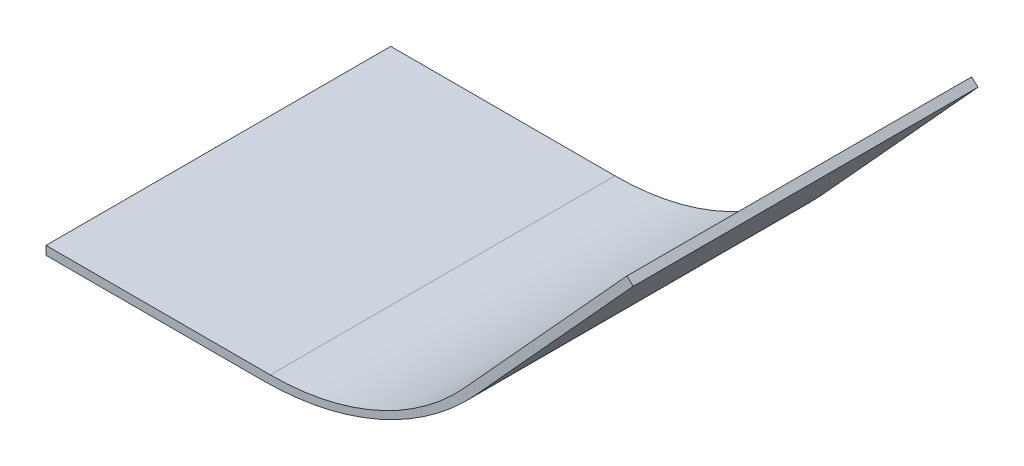
SolidWorks part; units mm, degrees
ref_plane "Front Plane" through (0, 0, 0) normal (0, 0, 1) x (1, 0, 0)
ref_plane "Top Plane" through (0, 0, 0) normal (0, 1, 0) x (1, 0, 0)
ref_plane "Right Plane" through (0, 0, 0) normal (1, 0, 0) x (0, 0, -1)
sketch "Sketch2" plane through (0, 0, 0) normal (0, 0, 1) x (1, 0, 0)
  line L0 (-10, 0.25) -> (-10, -0.25)
  line L1 (-10, 0.25) -> (3.0144, 0.25)
  line L2 (-10, -0.25) -> (2.5586, -0.25)
  line L4 (23.7043, 15.5673) -> (24.0738, 15.2305)
  line L5 (23.7043, 15.5673) -> (14.2726, 5.2211)
  line L6 (24.0738, 15.2305) -> (14.9492, 5.2211)
  arc A0 (2.5586, -0.25) -> (14.9492, 5.2211) centre (2.5586, 16.5164) ccw
  arc A1 (3.0144, 0.25) -> (14.2726, 5.2211) centre (3.0144, 15.4841) ccw
  point P14 (12.6919, 2.7449)
  point P15 (12.2182, 2.9674)
  point P16 (0, 0)
  point P17 (0, 0)
  point P18 (2.5586, 16.5164)
  point P19 (2.5586, -0.25)
  dimension "D1" = 14
extrude "Boss-Extrude1" add sketch "Sketch2" against normal blind 20
